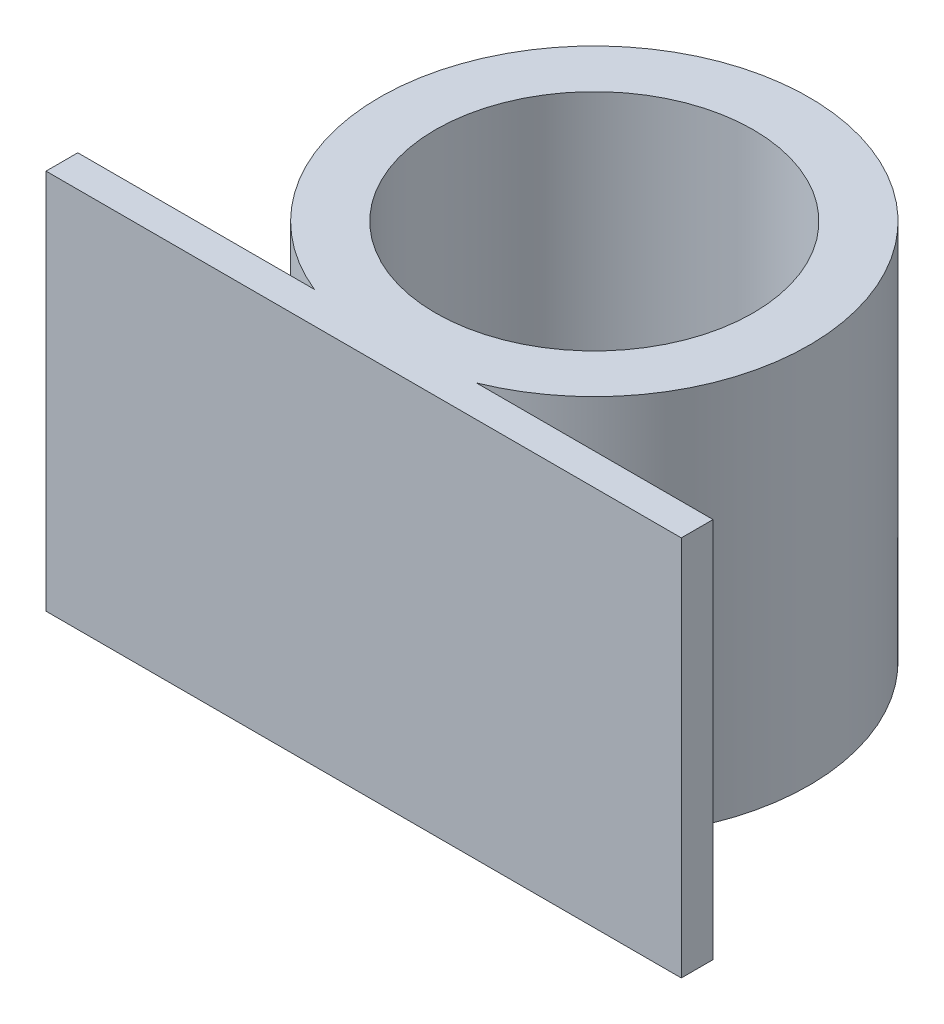
SolidWorks part; units mm, degrees
ref_plane "Front Plane" through (0, 0, 0) normal (0, 0, 1) x (1, 0, 0)
ref_plane "Top Plane" through (0, 0, 0) normal (0, 1, 0) x (1, 0, 0)
ref_plane "Right Plane" through (0, 0, 0) normal (1, 0, 0) x (0, 0, -1)
sketch "Sketch1" plane through (0, 0, 0) normal (0, 1, 0) x (1, 0, 0)
  line L5 (5.1037, -12.5241) -> (20, -12.5241)
  line L6 (-20, -12.5241) -> (-5.1037, -12.5241)
  line L7 (-20, -12.5241) -> (-20, -14.5241)
  line L8 (-20, -14.5241) -> (20, -14.5241)
  line L9 (20, -12.5241) -> (20, -14.5241)
  circle A0 centre (0, 0) radius 10
  arc A1 (5.1037, -12.5241) -> (-5.1037, -12.5241) centre (0, 0) ccw
  point P4 (0, -13.5241)
  dimension "D1" = 2
  dimension "D3" = 20
  dimension "D2" = 40
extrude "Boss-Extrude1" add sketch "Sketch1" along normal blind 20
sketch "Sketch2" plane through (0, 0, 0) normal (0, -1, 0) x (1, 0, 0)
  line L0 (5.1037, 12.5241) -> (20, 12.5241)
  line L1 (-20, 14.5241) -> (20, 14.5241)
  line L2 (-20, 14.5241) -> (-20, 12.5241)
  line L3 (-20, 12.5241) -> (-5.1037, 12.5241)
  line L4 (20, 14.5241) -> (20, 12.5241)
  arc A0 (-5.1037, 12.5241) -> (5.1037, 12.5241) centre (0, 0) ccw
extrude "Boss-Extrude2" add sketch "Sketch2" along normal blind 4
